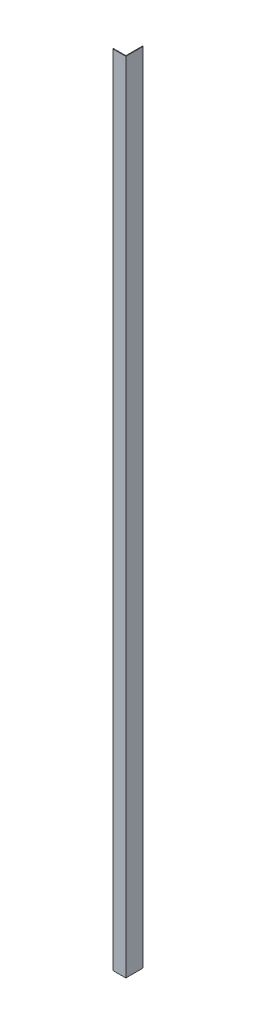
SolidWorks part; units mm, degrees
ref_plane "Front Plane" through (0, 0, 0) normal (0, 0, 1) x (1, 0, 0)
ref_plane "Top Plane" through (0, 0, 0) normal (0, 1, 0) x (1, 0, 0)
ref_plane "Right Plane" through (0, 0, 0) normal (1, 0, 0) x (0, 0, -1)
other "Configuration Table"
sketch "Sketch1" plane through (0, 0, 0) normal (0, 1, 0) x (1, 0, 0)
  line L0 (0, -40) -> (0, -38.5)
  line L1 (0, -38.5) -> (28.5, -38.5)
  line L2 (28.5, -38.5) -> (28.5, 0)
  line L3 (28.5, 0) -> (30, 0)
  line L4 (30, 0) -> (30, -40)
  line L5 (30, -40) -> (0, -40)
extrude "PACK_sove_sol_1" add sketch "Sketch1" along normal blind 1850 from offset 120 separate body
